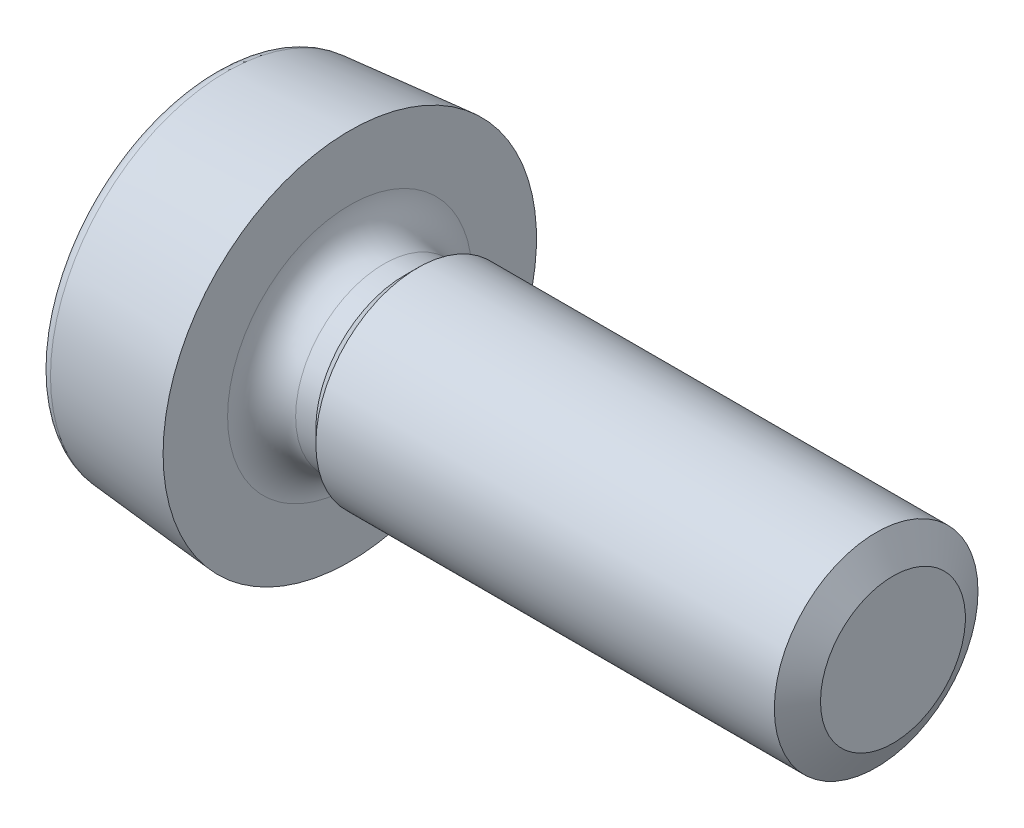
SolidWorks part; units mm, degrees
revolve "基体-旋转" add sketch "草图3" angle 360 about L0
sketch "草图3" plane through (0, 0, 0) normal (0, 0, 1) x (1, 0, 0)
  line L0 (-2.1696, 0) -> (16.014, 0) construction
  line L1 (0, 0) -> (10, 0)
  line L2 (10, 0) -> (10, 1.5)
  line L3 (10, 1.5) -> (3, 1.5)
  line L4 (3, 1.5) -> (2.799, 1.299)
  line L5 (2.799, 1.299) -> (2.501, 1.299)
  line L7 (2, 2.75) -> (0.1826, 2.591)
  line L8 (0, 2.3918) -> (0, 0)
  line L9 (2, 1.8) -> (2, 2.75)
  arc A0 (2, 1.8) -> (2.501, 1.299) centre (2.501, 1.8) ccw
  arc A1 (0.1826, 2.591) -> (0, 2.3918) centre (0.2, 2.3918) ccw
  dimension "D4" = 0.2
  dimension "D1" = 5
  dimension "dk" = 5.5
  dimension "d" = 3
  dimension "D2" = 45
  dimension "da" = 3.6
  dimension "k" = 2
  dimension "D3" = 2.598
  dimension "a" = 1
  dimension "l" = 8
cosmetic thread "装饰螺纹线1" parameters "D2"=2.598
material "AISI 304"
ref_plane "前视" through (0, 0, 0) normal (0, 0, 1) x (1, 0, 0)
ref_plane "上视" through (0, 0, 0) normal (0, 1, 0) x (1, 0, 0)
ref_plane "右视" through (0, 0, 0) normal (1, 0, 0) x (0, 0, -1)
sketch "尺寸草图" plane through (0, 0, 0) normal (0, 0, 1) x (1, 0, 0)
  line L0 (0, 0) -> (8, 0)
  line L1 (0, 0) -> (0, 5.5)
  line L2 (8, 0) -> (8, 3)
  point P5 (0, 3.6)
  point P6 (2, 0)
  point P7 (3, 0)
  point P8 (7.5, 0)
  point P9 (7.14, 0)
  point P10 (4.5, 0)
  point P11 (0, 0.1)
  dimension "dk" = 5.5
  dimension "d" = 3
  dimension "da" = 3.6
  dimension "k" = 2
  dimension "a" = 1
  dimension "l" = 8
  dimension "P" = 0.5
  dimension "h" = 0.86
  dimension "m" = 3.5
  dimension "r" = 0.1
sketch "草图4" plane through (0, 0, 0) normal (0, 0, 1) x (1, 0, 0)
  line L0 (9.7527, 1.5) -> (10.2527, 1.5)
  line L1 (10.2527, 1.5) -> (10, 1.067)
  line L2 (10, 1.067) -> (9.7527, 1.5)
  line L3 (10, 1.5) -> (3, 1.5) construction
  line L4 (10, -1.5) -> (10, 1.5) construction
  line L5 (-0.218, 0) -> (14.7427, 0) construction
  line L6 (-2.1696, 0) -> (16.014, 0) construction
  dimension "D1" = 0.5
  dimension "D2" = 0.433
  dimension "D3" = 60
revolve "切除-旋转1" cut sketch "草图4" angle 360 about L5
pattern_linear "阵列(线性)1" [suppressed] count 14 spacing 0.5 along (1, 0, 0)
sketch "草图5" plane through (0, 0, 0) normal (-1, 0, 0) x (0, 0, 1)
  line L1 (-0.25, 1.75) -> (0.25, 1.75)
  line L2 (-0.25, 1.75) -> (-0.25, -1.75)
  line L3 (-0.25, -1.75) -> (0.25, -1.75)
  line L4 (0.25, 1.75) -> (0.25, -1.75)
  point P4 (-0.25, 0)
  point P5 (0, 1.75)
  dimension "m" = 3.5
  dimension "D1" = 0.5
ref_plane "基准面1" through (0.86, 0, 0) normal (1, 0, 0) x (0, 0, -1)
sketch "草图6" plane through (0.86, 0, 0) normal (1, 0, 0) x (0, 0, -1)
  point P0 (0, 0)
loft "切除-放样1" cut profiles "草图5", "草图6"
pattern_circular "阵列(圆周)1" count 2 every 90 about axis through (0, 0, 0) along (1, 0, 0) of "切除-放样1"
equation "\"l@草图3\" = \"l@尺寸草图\""
equation "\"dk@草图3\" = \"dk@尺寸草图\""
equation "\"da@草图3\" = \"da@尺寸草图\""
equation "\"D4@草图3\" = \"r@尺寸草图\"*2"
equation "\"k@草图3\" = \"k@尺寸草图\""
equation "\"a@草图3\" = \"a@尺寸草图\""
equation "\"D3@草图3\" = \"d@尺寸草图\"*0.866"
equation "\"d@草图3\" = \"d@尺寸草图\""
equation "\"D2@装饰螺纹线1\" = \"d@尺寸草图\"*0.866"
equation "\"D1@草图4\" = \"P@尺寸草图\""
equation "\"D2@草图4\" = \"P@尺寸草图\"*0.866"
equation "\"D3@阵列(线性)1\" = \"P@尺寸草图\""
equation "\"D1@阵列(线性)1\" = (\"l@尺寸草图\"-\"a@尺寸草图\")/\"P@尺寸草图\""
equation "\"D1@基准面1\" = \"h@尺寸草图\""
equation "\"m@草图5\" = \"m@尺寸草图\""
equation "\"D1@草图5\" = \"P@尺寸草图\""
